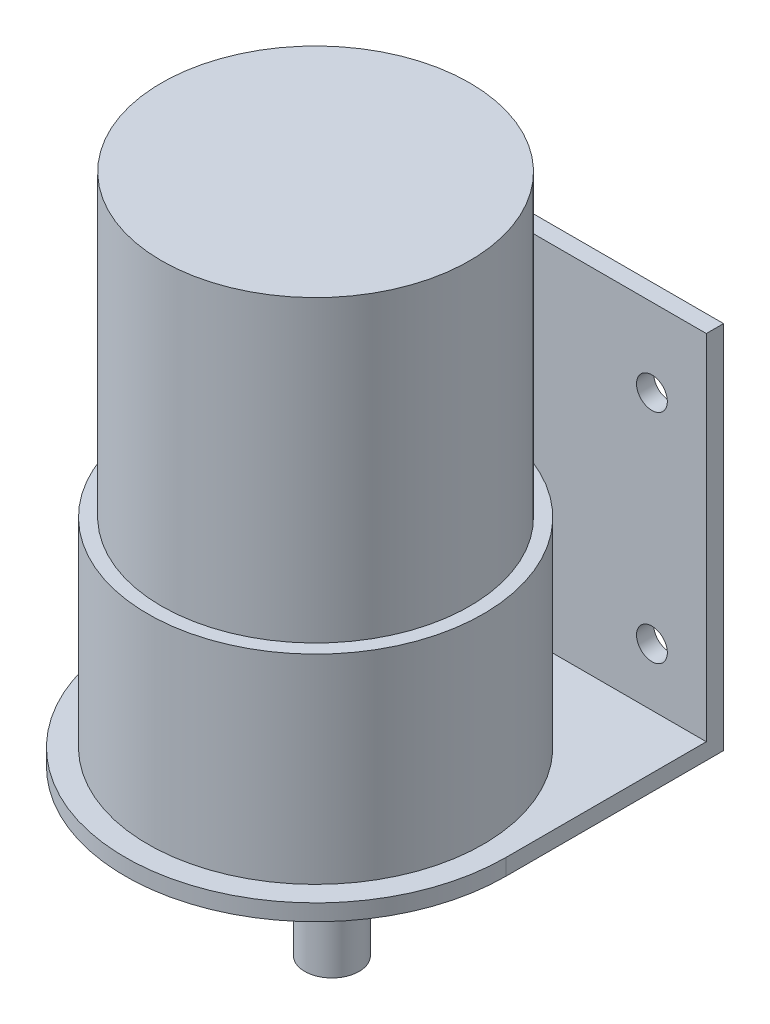
SolidWorks part; units mm, degrees
ref_plane "前视基准面" through (0, 0, 0) normal (0, 0, 1) x (1, 0, 0)
ref_plane "上视基准面" through (0, 0, 0) normal (0, 1, 0) x (1, 0, 0)
ref_plane "右视基准面" through (0, 0, 0) normal (1, 0, 0) x (0, 0, -1)
other "Configuration Table"
sketch "草图1" plane through (0, 0, 0) normal (0, 1, 0) x (1, 0, 0)
  circle A0 centre (0, 0) radius 17
  dimension "D1" = 34
extrude "凸台-拉伸1" add sketch "草图1" along normal blind 33
sketch "草图2" plane through (0, 0, 0) normal (0, -1, 0) x (1, 0, 0)
  circle A0 centre (0, 0) radius 18.5
  dimension "D1" = 37
extrude "凸台-拉伸2" add sketch "草图2" along normal blind 22
sketch "草图3" plane through (0, -22, 0) normal (0, -1, 0) x (1, 0, 0)
  line L0 (0, 0) -> (-21, 0) construction
  line L1 (0, 0) -> (21, 0) construction
  line L2 (-21, 0) -> (-21, -24)
  line L3 (21, 0) -> (21, -24)
  line L4 (21, -24) -> (-21, -24)
  circle A0 centre (0, 0) radius 18.5 construction
  circle A3 centre (0, 0) radius 21
  arc A4 (21, 0) -> (-21, 0) centre (0, 0) ccw
  dimension "D3" = 2.5
  dimension "D4" = 21
  dimension "D2" = 24
  dimension "D1" = 2.5
extrude "凸台-拉伸3" add sketch "草图3" along normal blind 1.8
sketch "草图4" plane through (0, -22, 0) normal (0, 1, 0) x (1, 0, 0)
  line L0 (-21, 24) -> (-21, 22.1)
  line L1 (-21, 24) -> (21, 24)
  line L2 (21, 24) -> (21, 22.1)
  line L3 (21, 24) -> (21, 0) construction
  line L4 (21, 22.1) -> (-21, 22.1)
  dimension "D1" = 1.9
extrude "凸台-拉伸4" add sketch "草图4" along normal blind 39
sketch "草图5" plane through (0, -23.8, 0) normal (0, -1, 0) x (1, 0, 0)
  line L0 (0, 21) -> (0, -1.8) construction
  arc A0 (21, 0) -> (-21, 0) centre (0, 0) ccw construction
  circle A1 centre (0, -1.8) radius 6
  dimension "D2" = 12
  dimension "D1" = 22.8
extrude "凸台-拉伸5" add sketch "草图5" along normal blind 4
sketch "草图6" plane through (0, -27.8, 0) normal (0, -1, 0) x (1, 0, 0)
  circle A0 centre (0, -1.8) radius 3
  dimension "D1" = 6
extrude "凸台-拉伸6" add sketch "草图6" along normal blind 15
sketch "草图7" plane through (0, 0, -24) normal (0, 0, -1) x (-1, 0, 0)
  line L0 (0, 17) -> (0, -3.65) construction
  line L1 (-21, 17) -> (21, 17) construction
  line L3 (-15, 8.35) -> (15, 8.35) construction
  line L4 (-15, 8.35) -> (-15, -15.65) construction
  line L5 (-15, -15.65) -> (15, -15.65) construction
  line L6 (15, 8.35) -> (15, -15.65) construction
  line L7 (-15, 8.35) -> (15, -15.65) construction
  line L8 (-15, -15.65) -> (15, 8.35) construction
  circle A0 centre (-15, 8.35) radius 1.7
  circle A1 centre (-15, -15.65) radius 1.7
  circle A2 centre (15, 8.35) radius 1.7
  circle A3 centre (15, -15.65) radius 1.7
  dimension "D4" = 3.4
  dimension "D5" = 3.4
  dimension "D6" = 3.4
  dimension "D7" = 3.4
  dimension "D1" = 20.65
  dimension "D2" = 30
  dimension "D3" = 24
extrude "切除-拉伸1" cut sketch "草图7" against normal up to next
